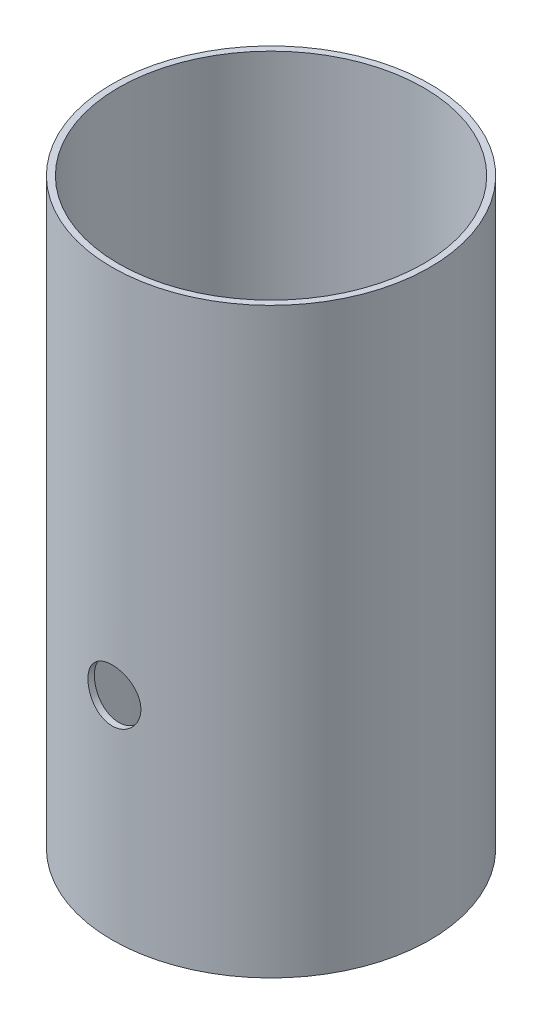
SolidWorks part; units mm, degrees
ref_plane "前视基准面" through (0, 0, 0) normal (0, 0, 1) x (1, 0, 0)
ref_plane "上视基准面" through (0, 0, 0) normal (0, 1, 0) x (1, 0, 0)
ref_plane "右视基准面" through (0, 0, 0) normal (1, 0, 0) x (0, 0, -1)
other "Configuration Table"
sketch "草图1" plane through (0, 0, 0) normal (0, 1, 0) x (1, 0, 0)
  circle A0 centre (0, 0) radius 38.1
  circle A1 centre (0, 0) radius 36.576
  dimension "D1" = 76.2
  dimension "D2" = 73.152
extrude "凸台-拉伸1" add sketch "草图1" along normal mid plane 139.7
sketch "Sketch1" plane through (0, 0, 0) normal (1, 0, 0) x (0, 0, -1)
  circle A0 centre (0, -19.05) radius 6.35
  dimension "D1" = 12.7
extrude "Cut-Extrude1" cut sketch "Sketch1" against normal through all
pattern_circular "CirPattern1" count 2 over 90 about axis through (0, -69.85, 0) along (0, 1, 0) of "Cut-Extrude1"
equation "\"airframeInnerDiameter\"=3"
equation "\"outerDiameter\"=3.124"
equation "\"airframeBulkheadThickness\"=0.125"
equation "\"payloadAirframeLength\"=5"
equation "\"payloadCouplerInnerDiameter\"=2.88"
equation "\"payloadCouplerLength\"=5.5"
equation "\"payloadCouplerBandLength\"=1"
equation "\"payloadCouplerOuter\"=\"airframeInnerDiameter\""
equation "\"payloadCouplerOffsetFromAft\"=3"
equation "\"upperAirframeLength\"=12.5"
equation "\"recoveryBayInnerDiameter\"=2.88"
equation "\"recoveryBayLength\"=4"
equation "\"recoveryBandLength\"=1"
equation "\"recoveryCouplerOuter\"=\"airframeInnerDiameter\""
equation "\"recoveryOffsetFromAft\"=1.5"
equation "\"midAirframeLength\"=10"
equation "\"ATSBayInnerDiameter\"=2.88"
equation "\"ATSBayLength\"=5.5"
equation "\"ATSBandLength\"=1"
equation "\"ATSCouplerOuter\"=\"airframeInnerDiameter\""
equation "\"ATSOffsetFromAft\"=1.5"
equation "\"lowerAirframeLength\"=20"
equation "\"finSlotLength\"=4.1875"
equation "\"finSlotOffsetFromAft\"=1.5"
equation "\"finSlotWidth\"=0.125"
equation "\"D1@草图1\"=\"airframeInnerDiameter\""
equation "\"D2@草图1\"=\"payloadCouplerInnerDiameter\""
equation "\"D1@凸台-拉伸1\"=\"payloadCouplerLength\""
